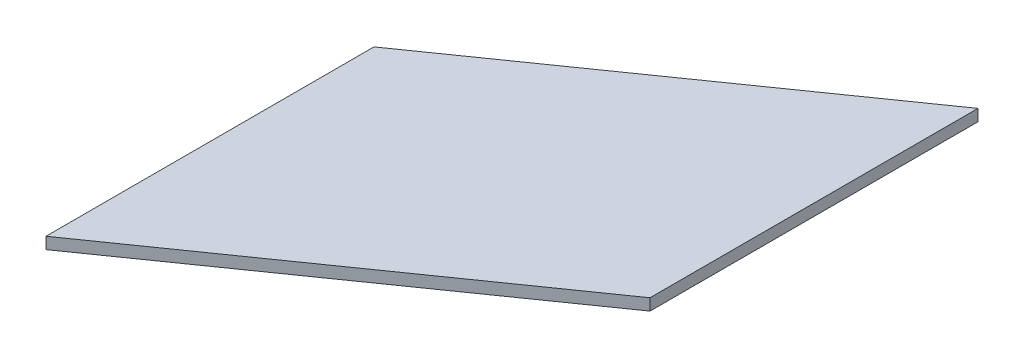
SolidWorks part; units mm, degrees
material "ABS PC"
ref_plane "Front" through (0, 0, 0) normal (0, 0, 1) x (1, 0, 0)
ref_plane "Top" through (0, 0, 0) normal (0, 1, 0) x (1, 0, 0)
ref_plane "Right" through (0, 0, 0) normal (1, 0, 0) x (0, 0, -1)
sketch "Sketch1" plane through (0, 0, 0) normal (0, 1, 0) x (1, 0, 0)
  line L0 (0, 0) -> (0, 359.0634)
  line L1 (0, 0) -> (388.9375, 272.337)
  line L2 (388.9375, 272.337) -> (388.9375, 631.4004)
  line L3 (0, 38.7596) -> (388.9375, 311.0966) construction
  line L4 (0, 54.2634) -> (388.9375, 326.6004) construction
  line L5 (0, 0) -> (-115.0997, 0) construction
  line L6 (0, 359.0634) -> (388.9375, 631.4004)
  dimension "D1" = 388.9375
  dimension "D2" = 145
  dimension "D3" = 31.75
  dimension "D4" = 12.7
  dimension "D5" = 304.8
extrude "Boss-Extrude1" add sketch "Sketch1" along normal blind 12.7
sketch "Sketch2" plane through (0, 12.7, 0) normal (0, 1, 0) x (1, 0, 0)
  line L0 (0, 38.7596) -> (388.9375, 311.0966) construction
  line L1 (0, 359.0634) -> (0, 0) construction
  line L2 (388.9375, 272.337) -> (388.9375, 631.4004) construction
  line L3 (0, 55.1937) -> (388.9375, 327.5306) construction
  line L4 (0, 0) -> (388.9375, 272.337) construction
  line L5 (35.0561, 79.7402) -> (60.9887, 42.7047)
  line L6 (0, 55.1937) -> (35.0561, 79.7402)
  line L7 (0, 55.1937) -> (0, 0)
  line L8 (0, 0) -> (60.9887, 42.7047)
  line L9 (388.9375, 327.5306) -> (346.0997, 297.5353)
  line L10 (346.0997, 297.5353) -> (372.0322, 260.4998)
  line L11 (372.0322, 260.4998) -> (388.9375, 272.337)
  line L12 (388.9375, 272.337) -> (388.9375, 327.5306)
  dimension "D1" = 31.75
  dimension "D2" = 13.462
  dimension "D3" = 74.4534
  dimension "D4" = 20.6375
extrude "Cut-Extrude1" [suppressed] cut sketch "Sketch2" against normal through all
sketch "Sketch3" [suppressed] plane through (0, 12.7, 0) normal (0, 1, 0) x (1, 0, 0)
  line L0 (54.6148, 51.8076) -> (365.6584, 269.6026) construction
  line L1 (60.9887, 42.7047) -> (35.0561, 79.7402) construction
  line L2 (346.0997, 297.5353) -> (372.0322, 260.4998) construction
  line L3 (60.9887, 42.7047) -> (372.0322, 260.4998) construction
  line L4 (25.4, 340.9437) -> (25.4, 99.6437) construction
  line L5 (0, 359.0634) -> (0, 55.1937) construction
  line L6 (363.5375, 580.6004) -> (363.5375, 339.3004) construction
  line L7 (388.9375, 327.5306) -> (388.9375, 631.4004) construction
  circle A0 centre (210.1366, 160.7051) radius 3.3782
  circle A1 centre (334.9754, 248.1181) radius 3.3782
  circle A2 centre (85.2978, 73.292) radius 3.3782
  circle A3 centre (25.4, 99.6437) radius 6.35
  circle A4 centre (25.4, 340.9437) radius 6.35
  circle A5 centre (363.5375, 339.3004) radius 6.35
  circle A6 centre (363.5375, 580.6004) radius 6.35
  dimension "D2" = 6.7564
  dimension "D5" = 12.7
  dimension "D1" = 11.1125
  dimension "D3" = 152.4
  dimension "D4" = 152.4
  dimension "D6" = 25.4
  dimension "D7" = 44.45
  dimension "D8" = 241.3
  dimension "D9" = 25.4
  dimension "D10" = 50.8
extrude "Cut-Extrude2" [suppressed] cut sketch "Sketch3" against normal through all
fillet "Fillet1" [suppressed] radius 6.604
